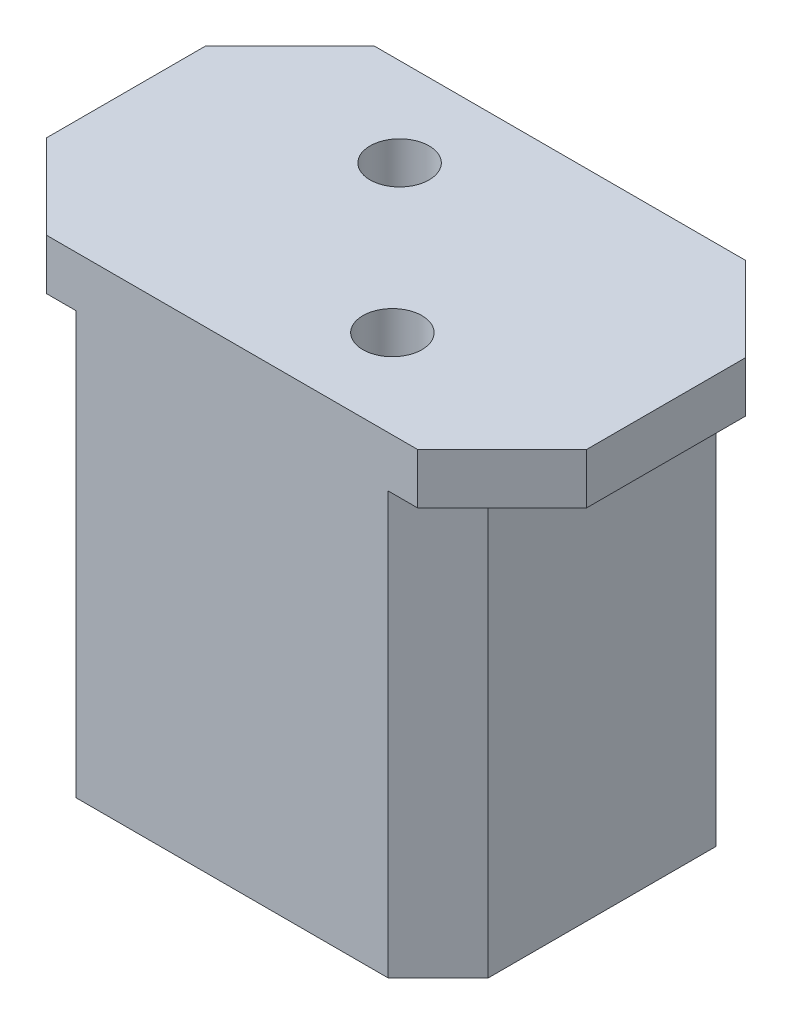
SolidWorks part; units mm, degrees
ref_plane "Front Plane" through (0, 0, 0) normal (0, 0, 1) x (1, 0, 0)
ref_plane "Top Plane" through (0, 0, 0) normal (0, 1, 0) x (1, 0, 0)
ref_plane "Right Plane" through (0, 0, 0) normal (1, 0, 0) x (0, 0, -1)
sketch "Sketch2" plane through (0, 0, 0) normal (0, 1, 0) x (1, 0, 0)
  line L0 (0, 0) -> (0, 13.5)
  line L1 (0, 13.5) -> (2.9628, 16.4628)
  line L2 (2.9628, 16.4628) -> (21.4628, 16.4628)
  line L3 (21.4628, 16.4628) -> (24.4256, 13.5)
  line L4 (24.4256, 13.5) -> (24.4256, 0)
  line L5 (24.4256, 0) -> (21.4628, -2.9628)
  line L6 (21.4628, -2.9628) -> (2.9628, -2.9628)
  line L7 (2.9628, -2.9628) -> (0, 0)
  dimension "D1" = 18.5
  dimension "D2" = 13.5
  dimension "D3" = 4.19
extrude "Boss-Extrude1" add sketch "Sketch2" along normal blind 25
sketch "Sketch5" plane through (0, 0, 0) normal (0, -1, 0) x (-1, 0, 0)
  line L0 (-12.2128, 16.4628) -> (-12.2128, -2.9628) construction
  line L1 (-12.2128, 15.4628) -> (-3.7128, 15.4628)
  line L2 (-12.2128, 15.4628) -> (-12.2128, 6.9628)
  line L3 (-12.2128, 6.9628) -> (-3.7128, 6.9628)
  line L4 (-3.7128, 15.4628) -> (-3.7128, 6.9628)
  line L5 (-20.7128, 6.5372) -> (-12.2128, 6.5372)
  line L6 (-20.7128, 6.5372) -> (-20.7128, -1.9628)
  line L7 (-20.7128, -1.9628) -> (-12.2128, -1.9628)
  line L8 (-12.2128, 6.5372) -> (-12.2128, -1.9628)
  line L9 (-21.4628, 16.4628) -> (-2.9628, 16.4628) construction
  line L10 (-2.9628, -2.9628) -> (-21.4628, -2.9628) construction
  dimension "D1" = 8.5
  dimension "D2" = 1
  dimension "D3" = 1
extrude "Cut-Extrude1" cut sketch "Sketch5" against normal offset from surface (20 mm away) 5 up to face at (12.2128, 25, -6.75)
sketch "Sketch6" plane through (0, 20, 0) normal (0, -1, 0) x (-1, 0, 0)
  line L0 (-12.2128, 15.4628) -> (-3.7128, 6.9628) construction
  circle A0 centre (-7.9628, 11.2128) radius 1.75
  dimension "D1" = 3.5
extrude "Cut-Extrude2" cut sketch "Sketch6" against normal blind 13
sketch "Sketch7" plane through (0, 20, 0) normal (0, -1, 0) x (1, 0, 0)
  line L0 (12.2128, -6.5372) -> (20.7128, 1.9628) construction
  circle A0 centre (16.4628, -2.2872) radius 1.75
  dimension "D1" = 3.5
extrude "Cut-Extrude3" cut sketch "Sketch7" against normal blind 13
sketch "Sketch8" plane through (0, 25, 0) normal (0, 1, 0) x (1, 0, 0)
  line L0 (12.2128, 16.4628) -> (12.2128, -2.9628) construction
  line L1 (21.4628, 16.4628) -> (2.9628, 16.4628) construction
  line L2 (2.9628, -2.9628) -> (21.4628, -2.9628) construction
  line L4 (-3.7872, -2.9628) -> (28.2128, -2.9628)
  line L5 (-3.7872, -2.9628) -> (-3.7872, 16.4628)
  line L6 (-3.7872, 16.4628) -> (28.2128, 16.4628)
  line L7 (28.2128, -2.9628) -> (28.2128, 16.4628)
  line L8 (-3.7872, -2.9628) -> (28.2128, 16.4628) construction
  line L9 (-3.7872, 16.4628) -> (28.2128, -2.9628) construction
  circle A0 centre (7.9628, 11.2128) radius 1.75
  circle A1 centre (16.4628, 2.2872) radius 1.75
  point P6 (12.2128, 6.75)
  dimension "D1" = 32
extrude "Boss-Extrude2" add sketch "Sketch8" along normal blind 3
chamfer "Chamfer3" distance 5 angle 45 4 edges at (28.2128, 26.5, 2.9628) (-3.7872, 26.5, 2.9628) (-3.7872, 26.5, -16.4628) (28.2128, 26.5, -16.4628)
